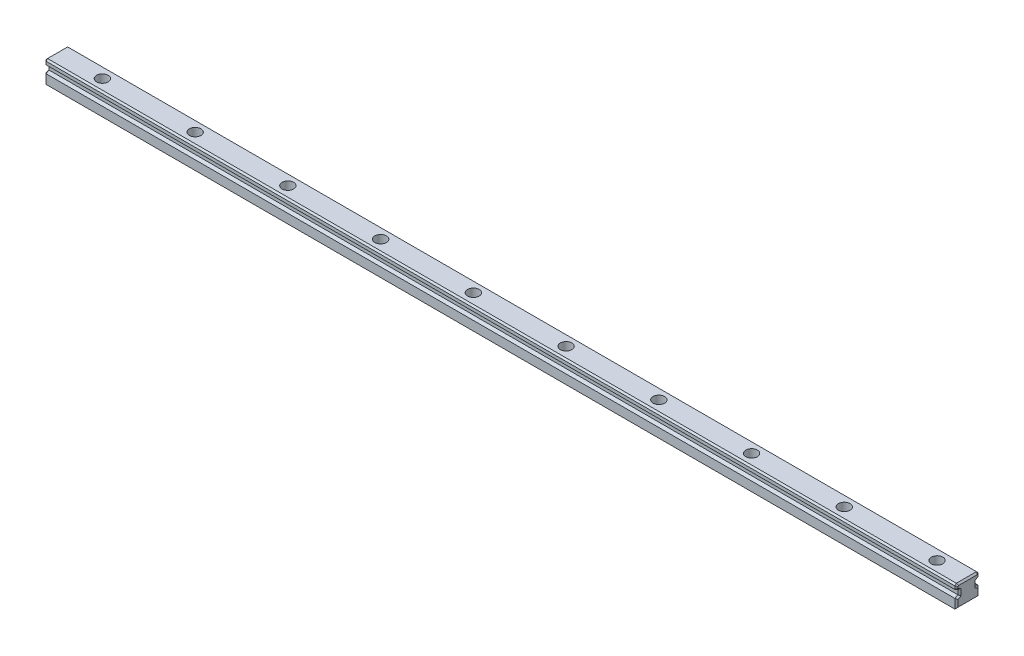
SolidWorks part; units mm, degrees
material "Chrome Stainless Steel"
ref_plane "Front Plane" through (0, 0, 0) normal (0, 0, 1) x (1, 0, 0)
ref_plane "Top Plane" through (0, 0, 0) normal (0, 1, 0) x (1, 0, 0)
ref_plane "Right Plane" through (0, 0, 0) normal (1, 0, 0) x (0, 0, -1)
sketch "Sketch1" plane through (0, 0, 0) normal (1, 0, 0) x (0, 0, -1)
  line L0 (0, 30.812) -> (0, -30.812) construction
  line L1 (-7.5, 0) -> (7.5, 0)
  line L2 (-6.5, 14) -> (6.5, 14)
  line L3 (-7.5, 14) -> (7.5, 14) construction
  line L4 (-6.5, 14) -> (-7.5, 13)
  line L5 (-7.5, 13) -> (-7.5, 11)
  line L6 (-7.5, 11) -> (-5.5, 10)
  line L7 (-5.5, 10) -> (-5.5, 7)
  line L8 (-5.5, 7) -> (-7.5, 6)
  line L9 (-7.5, 6) -> (-7.5, 0)
  line L10 (-7.5, 0) -> (7.5, 0) construction
  line L11 (7.5, 6) -> (7.5, 0)
  line L12 (5.5, 7) -> (7.5, 6)
  line L13 (5.5, 10) -> (5.5, 7)
  line L14 (7.5, 11) -> (5.5, 10)
  line L15 (7.5, 13) -> (7.5, 11)
  line L16 (6.5, 14) -> (7.5, 13)
  point P9 (0, 0)
  point P22 (0, 14)
  dimension "D3" = 1
  dimension "D4" = 1
  dimension "D5" = 7.5
  dimension "D6" = 2
  dimension "D7" = 1
  dimension "D8" = 2
  dimension "D9" = 3
  dimension "D10" = 6
  dimension "D2" = 14
extrude "Boss-Extrude1" add sketch "Sketch1" along normal blind 590
chamfer "Chamfer1" distance 1 angle 45 14 edges at (0, 0, 0) (0, 3, -7.5) (0, 6.5, -6.5) (0, 8.5, -5.5) (0, 10.5, -6.5) (0, 12, -7.5) (0, 13.5, -7) (0, 14, 0) (0, 13.5, 7) (0, 12, 7.5) (0, 10.5, 6.5) (0, 8.5, 5.5) (0, 6.5, 6.5) (0, 3, 7.5)
chamfer "Chamfer2" distance 1 angle 45 14 edges at (590, 6.5, 6.5) (590, 8.5, 5.5) (590, 10.5, 6.5) (590, 12, 7.5) (590, 13.5, 7) (590, 14, 0) (590, 13.5, -7) (590, 12, -7.5) (590, 10.5, -6.5) (590, 8.5, -5.5) (590, 6.5, -6.5) (590, 3, -7.5) (590, 0, 0) (590, 3, 7.5)
sketch "Sketch2" plane through (0, 14, 0) normal (0, 1, 0) x (1, 0, 0)
  line L0 (590, 6.0858) -> (590, -6.0858) construction
  circle A0 centre (570, 0) radius 3.75
  dimension "D2" = 7.5
  dimension "D1" = 20
extrude "Cut-Extrude1" cut sketch "Sketch2" against normal blind 5.3
sketch "Sketch3" plane through (0, 8.7, 0) normal (0, 1, 0) x (1, 0, 0)
  circle A0 centre (570, 0) radius 2.25
  dimension "D1" = 4.5
extrude "Cut-Extrude2" cut sketch "Sketch3" against normal through all
pattern_linear "LPattern1" count 67 spacing 60 along (-1, 0, 0) of "Cut-Extrude1", "Cut-Extrude2"
sketch "Sketch5" plane through (0, 14, 0) normal (0, 1, 0) x (1, 0, 0)
  text T0 "SHN 15 B" font "Century Gothic" height 3.5
